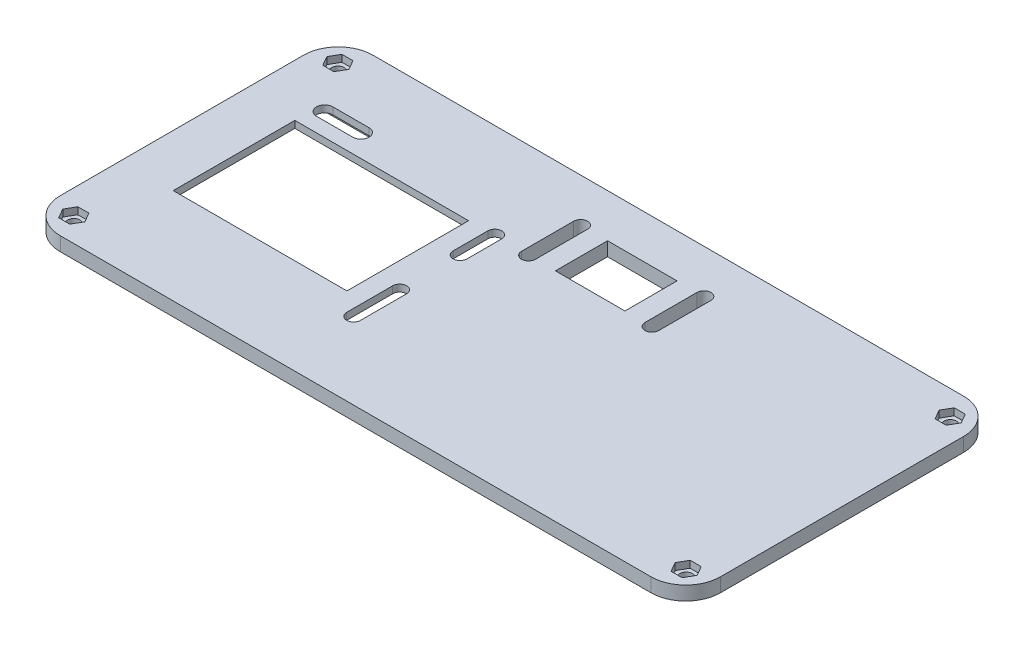
SolidWorks part; units mm, degrees
material "ABS"
ref_plane "Front Plane" through (0, 0, 0) normal (0, 0, 1) x (1, 0, 0)
ref_plane "Top Plane" through (0, 0, 0) normal (0, 1, 0) x (1, 0, 0)
ref_plane "Right Plane" through (0, 0, 0) normal (1, 0, 0) x (0, 0, -1)
sketch "Sketch1" plane through (0, 0, 0) normal (0, 1, 0) x (1, 0, 0)
  line L0 (0, 0) -> (0, 45) construction
  line L1 (-95, -45) -> (95, -45)
  line L2 (-95, -45) -> (-95, 45)
  line L3 (-95, 45) -> (95, 45)
  line L4 (95, -45) -> (95, 45)
  line L5 (-95, -45) -> (95, 45) construction
  line L6 (-95, 45) -> (95, -45) construction
  point P0 (0, 0)
  point P7 (0, 0)
  point P22 (0, 0)
  dimension "D13" = 190
  dimension "D14" = 90
extrude "Boss-Extrude1" add sketch "Sketch1" along normal blind 4
sketch "Sketch2" plane through (0, 4, 0) normal (0, 1, 0) x (1, 0, 0)
  line L1 (-95, 45) -> (95, 45) construction
  line L3 (-84.936, 38) -> (-86.5251, 40.7525)
  line L4 (-86.5251, 40.7525) -> (-89.7035, 40.7525)
  line L5 (-89.7035, 40.7525) -> (-91.2926, 38)
  line L6 (-91.2926, 38) -> (-89.7035, 35.2475)
  line L7 (-89.7035, 35.2475) -> (-86.5251, 35.2475)
  line L8 (-86.5251, 35.2475) -> (-84.936, 38)
  circle A1 centre (-88.1143, 38) radius 2.7525 construction
  circle A2 centre (-88.1143, 38) radius 1.75
  dimension "D1" = 3.5
  dimension "D3" = 7
extrude "Cut-Extrude8" cut sketch "Sketch2" against normal blind 2
sketch "Sketch14" plane through (0, 4, 0) normal (0, 1, 0) x (1, 0, 0)
  circle A0 centre (-88.1143, 38) radius 1.75
extrude "Cut-Extrude9" cut sketch "Sketch14" against normal blind 4
mirror "Mirror8" about plane through (0, 0, 0) normal (0, 0, 1) of "Cut-Extrude9", "Cut-Extrude8"
mirror "Mirror9" about plane through (0, 0, 0) normal (1, 0, 0) of "Mirror8", "Cut-Extrude8", "Cut-Extrude9"
sketch "Sketch16" plane through (0, 0, 0) normal (0, -1, 0) x (1, 0, 0)
  line L0 (-95, 45) -> (-95, -45) construction
  line L1 (-90.3, -28) -> (-19.7, -28)
  line L2 (-90.3, -28) -> (-90.3, 28)
  line L3 (-90.3, 28) -> (-19.7, 28)
  line L4 (-19.7, -28) -> (-19.7, 28)
  line L5 (-90.3, -28) -> (-19.7, 28) construction
  line L6 (-90.3, 28) -> (-19.7, -28) construction
  line L7 (-95, 45) -> (95, 45) construction
  point P0 (-55, 0)
  dimension "D1" = 70.6
  dimension "D2" = 56
  dimension "D3" = 40
  dimension "D4" = 45
extrude "Cut-Extrude10" cut sketch "Sketch16" against normal blind 2
sketch "Sketch17" plane through (0, 2, 0) normal (0, -1, 0) x (1, 0, 0)
  line L0 (-77.9107, -24) -> (-67.4893, -24) construction
  line L1 (-77.9107, -21.65) -> (-67.4893, -21.65)
  line L2 (-77.9107, -26.35) -> (-67.4893, -26.35)
  line L3 (-19.7, -28) -> (-19.7, 28) construction
  line L4 (-90.3, -28) -> (-19.7, -28) construction
  line L5 (-22.7, -17.7495) -> (-22.7, -7.7495) construction
  line L6 (-24.7, -17.7495) -> (-24.7, -7.7495)
  line L7 (-20.7, -17.7495) -> (-20.7, -7.7495)
  line L8 (-22.7, 22.8766) -> (-22.7, 9.6244) construction
  line L9 (-20.7, 22.8766) -> (-20.7, 9.6244)
  line L10 (-24.7, 22.8766) -> (-24.7, 9.6244)
  arc A0 (-77.9107, -21.65) -> (-77.9107, -26.35) centre (-77.9107, -24) ccw
  arc A1 (-67.4893, -26.35) -> (-67.4893, -21.65) centre (-67.4893, -24) ccw
  arc A2 (-24.7, -17.7495) -> (-20.7, -17.7495) centre (-22.7, -17.7495) ccw
  arc A3 (-20.7, -7.7495) -> (-24.7, -7.7495) centre (-22.7, -7.7495) ccw
  arc A4 (-20.7, 22.8766) -> (-24.7, 22.8766) centre (-22.7, 22.8766) ccw
  arc A5 (-24.7, 9.6244) -> (-20.7, 9.6244) centre (-22.7, 9.6244) ccw
  point P2 (-72.7, -24)
  point P13 (-22.7, -12.7495)
  point P20 (-22.7, 16.2505)
  dimension "D3" = 50
  dimension "D4" = 29
  dimension "D1" = 53
  dimension "D2" = 4
extrude "Cut-Extrude11" cut sketch "Sketch17" against normal blind 4
sketch "Sketch18" plane through (0, 2, 0) normal (0, -1, 0) x (1, 0, 0)
  line L0 (-55, 28) -> (-55, -28) construction
  line L1 (-19.7, 28) -> (-90.3, 28) construction
  line L2 (-90.3, -28) -> (-19.7, -28) construction
  line L4 (-80, -17.5) -> (-30, -17.5)
  line L5 (-80, -17.5) -> (-80, 17.5)
  line L6 (-80, 17.5) -> (-30, 17.5)
  line L7 (-30, -17.5) -> (-30, 17.5)
  line L8 (-80, -17.5) -> (-30, 17.5) construction
  line L9 (-80, 17.5) -> (-30, -17.5) construction
  point P6 (-55, 0)
  dimension "D1" = 50
  dimension "D2" = 35
extrude "Cut-Extrude12" cut sketch "Sketch18" against normal blind 4
sketch "Sketch19" plane through (0, 0, 0) normal (0, -1, 0) x (1, 0, 0)
  line L0 (-95, -45) -> (95, -45) construction
  line L1 (-17.25, -35.75) -> (27.25, -35.75)
  line L2 (-17.25, -35.75) -> (-17.25, -14.25)
  line L3 (-17.25, -14.25) -> (27.25, -14.25)
  line L4 (27.25, -35.75) -> (27.25, -14.25)
  line L5 (-17.25, -35.75) -> (27.25, -14.25) construction
  line L6 (-17.25, -14.25) -> (27.25, -35.75) construction
  line L7 (-95, 45) -> (-95, -45) construction
  line L8 (5, -14.25) -> (5, -25) construction
  line L9 (-17.25, -14.25) -> (-8.25, -14.25)
  line L10 (-17.25, -14.25) -> (-17.25, -35.75)
  line L11 (-17.25, -35.75) -> (-8.25, -35.75)
  line L12 (-8.25, -14.25) -> (-8.25, -35.75)
  line L13 (27.25, -35.75) -> (18.25, -35.75)
  line L14 (18.25, -14.25) -> (18.25, -35.75)
  line L15 (27.25, -14.25) -> (18.25, -14.25)
  line L16 (27.25, -14.25) -> (27.25, -35.75)
  point P0 (5, -25)
  dimension "D1" = 44.5
  dimension "D2" = 21.5
  dimension "D3" = 20
  dimension "D4" = 100
  dimension "D5" = 9
extrude "Boss-Extrude2" add sketch "Sketch19" along normal blind 2 contours L12 L3 L2 L1 | L3 L14 L1 L4
sketch "Sketch20" plane through (0, -2, 0) normal (0, -1, 0) x (1, 0, 0)
  line L3 (-12.75, -32.5) -> (-12.75, -17.5) construction
  line L4 (-14.75, -32.5) -> (-14.75, -17.5)
  line L5 (-10.75, -32.5) -> (-10.75, -17.5)
  line L9 (22.75, -32.5) -> (22.75, -17.5) construction
  line L10 (24.75, -32.5) -> (24.75, -17.5)
  line L11 (20.75, -32.5) -> (20.75, -17.5)
  arc A0 (-14.75, -32.5) -> (-10.75, -32.5) centre (-12.75, -32.5) ccw
  arc A1 (-10.75, -17.5) -> (-14.75, -17.5) centre (-12.75, -17.5) ccw
  arc A2 (24.75, -32.5) -> (20.75, -32.5) centre (22.75, -32.5) cw
  arc A3 (20.75, -17.5) -> (24.75, -17.5) centre (22.75, -17.5) cw
  point P8 (-12.75, -25)
  point P20 (22.75, -25)
extrude "Cut-Extrude13" cut sketch "Sketch20" against normal blind 6
fillet "Fillet1" radius 10 4 edges at (95, 2, -45) (95, 2, 45) (-95, 2, 45) (-95, 2, -45)
sketch "Sketch21" plane through (0, 0, 0) normal (0, -1, 0) x (1, 0, 0)
  line L0 (-90.3, 28) -> (-90.3, -28) construction
  line L1 (-90.3, 6) -> (-95, 6)
  line L3 (-90.3, 19) -> (-95, 19)
  line L4 (-95, 6) -> (-95, 19)
  line L7 (-95, 35) -> (-95, -35) construction
  line L8 (-85, -45) -> (85, -45) construction
  line L9 (-90.3, 19) -> (-90.3, 6)
  point P0 (-90.3, 12.5)
  point P2 (-90.3, 12.5)
  dimension "D1" = 57.5
  dimension "D2" = 13
extrude "Cut-Extrude14" cut sketch "Sketch21" against normal blind 2
sketch "Sketch22" plane through (0, 0, 0) normal (0, -1, 0) x (1, 0, 0)
  line L0 (-8.25, -25) -> (18.25, -25) construction
  line L1 (-8.25, -14.25) -> (-8.25, -35.75) construction
  line L2 (18.25, -14.25) -> (18.25, -35.75) construction
  line L4 (-5, -32.5) -> (15, -32.5)
  line L5 (-5, -32.5) -> (-5, -17.5)
  line L6 (-5, -17.5) -> (15, -17.5)
  line L7 (15, -32.5) -> (15, -17.5)
  line L8 (-5, -32.5) -> (15, -17.5) construction
  line L9 (-5, -17.5) -> (15, -32.5) construction
  point P6 (5, -25)
  dimension "D1" = 20
  dimension "D2" = 15
extrude "Cut-Extrude15" cut sketch "Sketch22" against normal blind 4
sketch "Sketch23" plane through (0, 0, 0) normal (0, -1, 0) x (1, 0, 0)
  line L0 (-90.3, 6) -> (-90.3, -28) construction
  line L1 (-90.3, -23) -> (-95, -23)
  line L2 (-90.3, -23) -> (-90.3, -12)
  line L3 (-90.3, -12) -> (-95, -12)
  line L4 (-95, -23) -> (-95, -12)
  line L5 (-95, 6) -> (-95, -35) construction
  line L6 (-85, -45) -> (85, -45) construction
  dimension "D1" = 22
  dimension "D2" = 11
extrude "Cut-Extrude16" cut sketch "Sketch23" against normal blind 2
